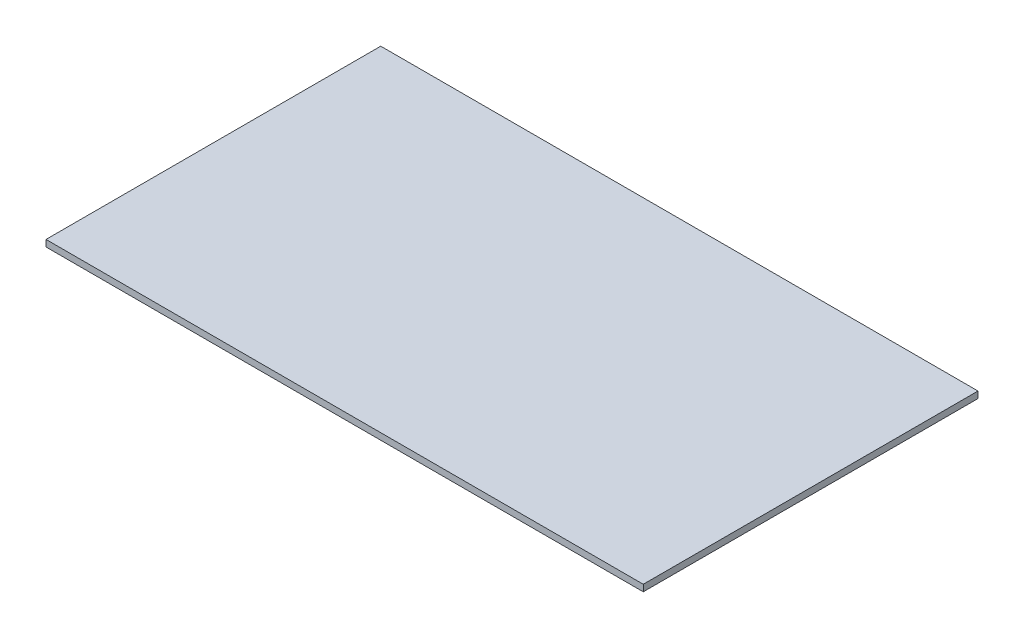
SolidWorks part; units mm, degrees
ref_plane "Front Plane" through (0, 0, 0) normal (0, 0, 1) x (1, 0, 0)
ref_plane "Top Plane" through (0, 0, 0) normal (0, 1, 0) x (1, 0, 0)
ref_plane "Right Plane" through (0, 0, 0) normal (1, 0, 0) x (0, 0, -1)
sketch "Sketch1" plane through (0, 0, 0) normal (0, 1, 0) x (1, 0, 0)
  line L1 (-227.5, -127.5) -> (227.5, -127.5)
  line L2 (-227.5, -127.5) -> (-227.5, 127.5)
  line L3 (-227.5, 127.5) -> (227.5, 127.5)
  line L4 (227.5, -127.5) -> (227.5, 127.5)
  line L5 (-227.5, -127.5) -> (227.5, 127.5) construction
  line L6 (-227.5, 127.5) -> (227.5, -127.5) construction
  point P0 (0, 0)
  dimension "D1" = 455
  dimension "D2" = 255
extrude "Boss-Extrude1" add sketch "Sketch1" along normal blind 5
